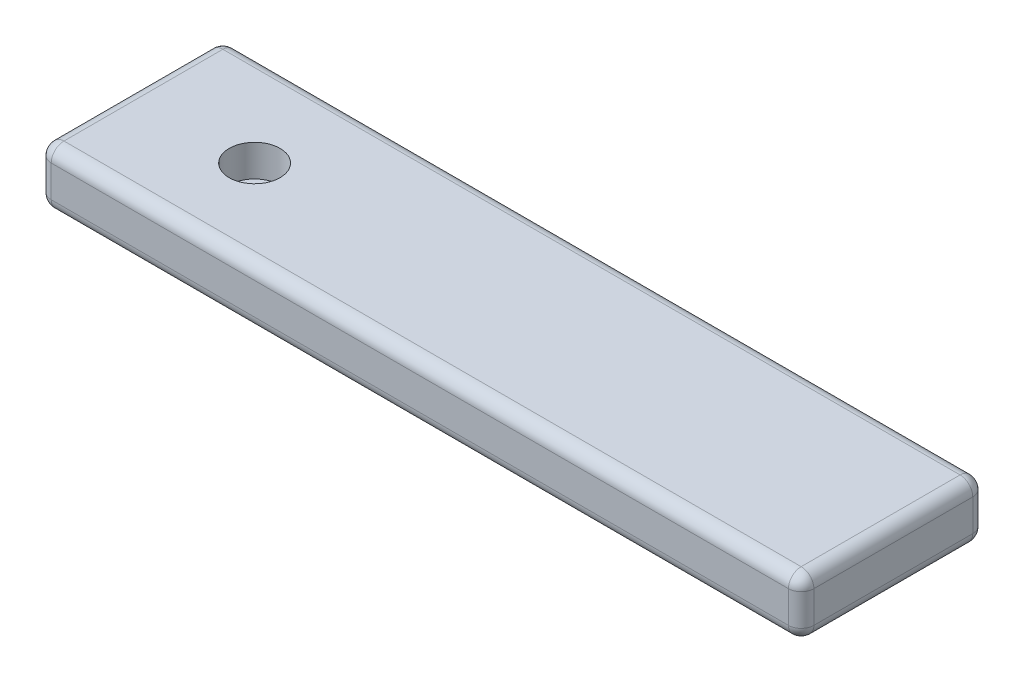
SolidWorks part; units mm, degrees
ref_plane "Front Plane" through (0, 0, 0) normal (0, 0, 1) x (1, 0, 0)
ref_plane "Top Plane" through (0, 0, 0) normal (0, 1, 0) x (1, 0, 0)
ref_plane "Right Plane" through (0, 0, 0) normal (1, 0, 0) x (0, 0, -1)
sketch "Sketch1" plane through (0, 0, 0) normal (1, 0, 0) x (0, 0, -1)
  line L1 (0, 0) -> (18.415, 0)
  line L2 (0, 0) -> (0, 5.715)
  line L3 (0, 5.715) -> (18.415, 5.715)
  line L4 (18.415, 0) -> (18.415, 5.715)
  dimension "D1" = 18.415
  dimension "D2" = 5.715
extrude "Boss-Extrude1" add sketch "Sketch1" along normal blind 76.2
sketch "Sketch2" plane through (0, 5.715, 0) normal (0, 1, 0) x (1, 0, 0)
  line L0 (76.2, 18.415) -> (0, 18.415) construction
  line L1 (0, 18.415) -> (0, 0) construction
  circle A0 centre (12.7, 8.89) radius 2.54
  dimension "D1" = 5.08
  dimension "D2" = 9.525
  dimension "D3" = 12.7
extrude "Cut-Extrude1" cut sketch "Sketch2" against normal blind 3.175
fillet "Fillet1" radius 1.27 12 edges at (76.2, 2.8575, 0) (76.2, 2.8575, -18.415) (0, 2.8575, 0) (0, 2.8575, -18.415) (38.1, 0, 0) (76.2, 0, -9.2075) (38.1, 0, -18.415) (0, 0, -9.2075) (38.1, 5.715, -18.415) (76.2, 5.715, -9.2075) (38.1, 5.715, 0) (0, 5.715, -9.2075)
